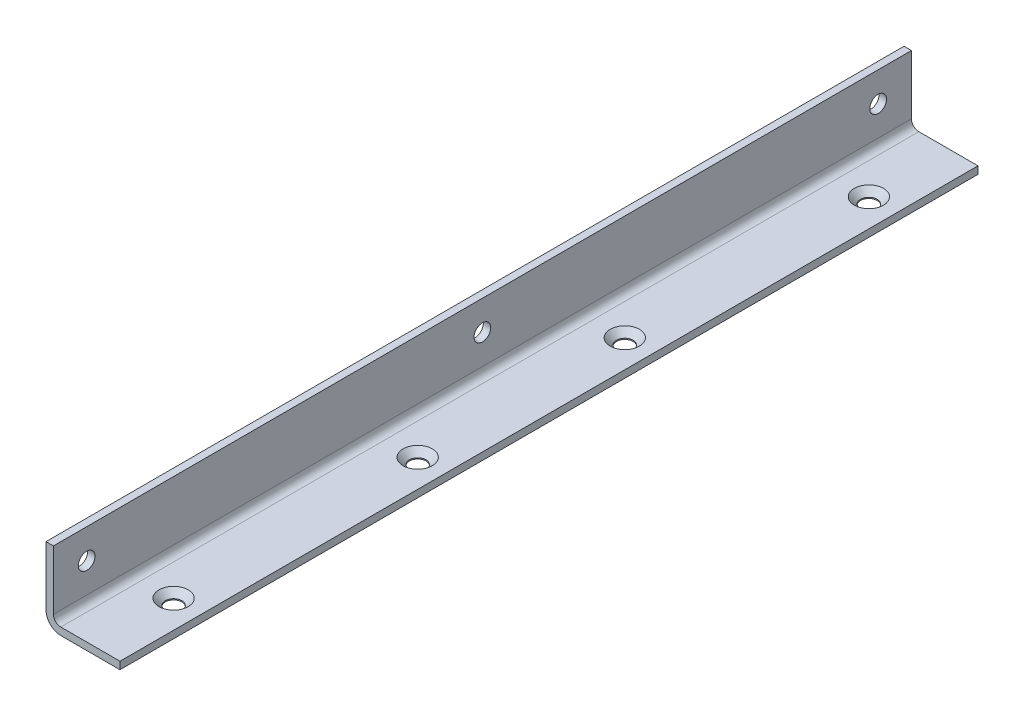
SolidWorks part; units mm, degrees
ref_plane "Спереди" through (0, 0, 0) normal (0, 0, 1) x (1, 0, 0)
ref_plane "Сверху" through (0, 0, 0) normal (0, 1, 0) x (1, 0, 0)
ref_plane "Справа" through (0, 0, 0) normal (1, 0, 0) x (0, 0, -1)
sketch "Эскиз1" plane through (0, 0, 0) normal (0, 0, 1) x (1, 0, 0)
  line L1 (0, 0) -> (20, 0)
  line L2 (0, 0) -> (0, 20)
  line L3 (0, 20) -> (2, 20)
  line L4 (20, 0) -> (20, 2)
  line L5 (4, 2) -> (20, 2)
  line L6 (2, 4) -> (2, 20)
  arc A0 (4, 2) -> (2, 4) centre (4, 4) cw
  dimension "D5" = 2
  dimension "D1" = 20
  dimension "D2" = 20
  dimension "D3" = 2
  dimension "D4" = 2
extrude "Вытянуть1" add sketch "Эскиз1" along normal blind 232
sketch "Эскиз2" plane through (2, 0, 0) normal (1, 0, 0) x (0, 0, -1)
  line L1 (-116, 12) -> (-116, 92.714) construction
  line L2 (-232, 4) -> (-232, 20) construction
  line L3 (-280.1291, 12) -> (26.6955, 12) construction
  line L4 (-232, 20) -> (0, 20) construction
  line L5 (0, 4) -> (0, 20) construction
  circle A0 centre (-223, 12) radius 2.25
  circle A1 centre (-9, 12) radius 2.25
  circle A2 centre (-116, 12) radius 2.25
  dimension "D2" = 4.5
  dimension "D5" = 107
  dimension "D4" = 214
  dimension "D1" = 8
extrude "Вырез-Вытянуть1" cut sketch "Эскиз2" against normal blind 10
sketch "Эскиз3" plane through (0, 2, 0) normal (0, 1, 0) x (1, 0, 0)
  line L0 (-101.7059, -116) -> (103.8615, -116) construction
  line L1 (20, 0) -> (4, 0) construction
  line L2 (20, -232) -> (4, -232) construction
  line L4 (12.5, -210) -> (12.5, -22) construction
  line L5 (20, -232) -> (20, 0) construction
  circle A1 centre (12.5, -210) radius 2.25
  circle A2 centre (12.5, -144) radius 2.25
  circle A5 centre (12.5, -22) radius 2.25
  circle A8 centre (12.5, -88) radius 2.25
  dimension "D1" = 66
  dimension "D2" = 4.5
  dimension "D3" = 7.5
  dimension "D4" = 56
extrude "Вырез-Вытянуть2" cut sketch "Эскиз3" against normal blind 10
chamfer "Фаска1" distance 1.7 angle 45 4 edges at (12.5, 2, 19.75) (12.5, 2, 90.25) (12.5, 2, 141.75) (12.5, 2, 212.25)
fillet "Скругление1" radius 4 1 edges at (0, 0, 116)
